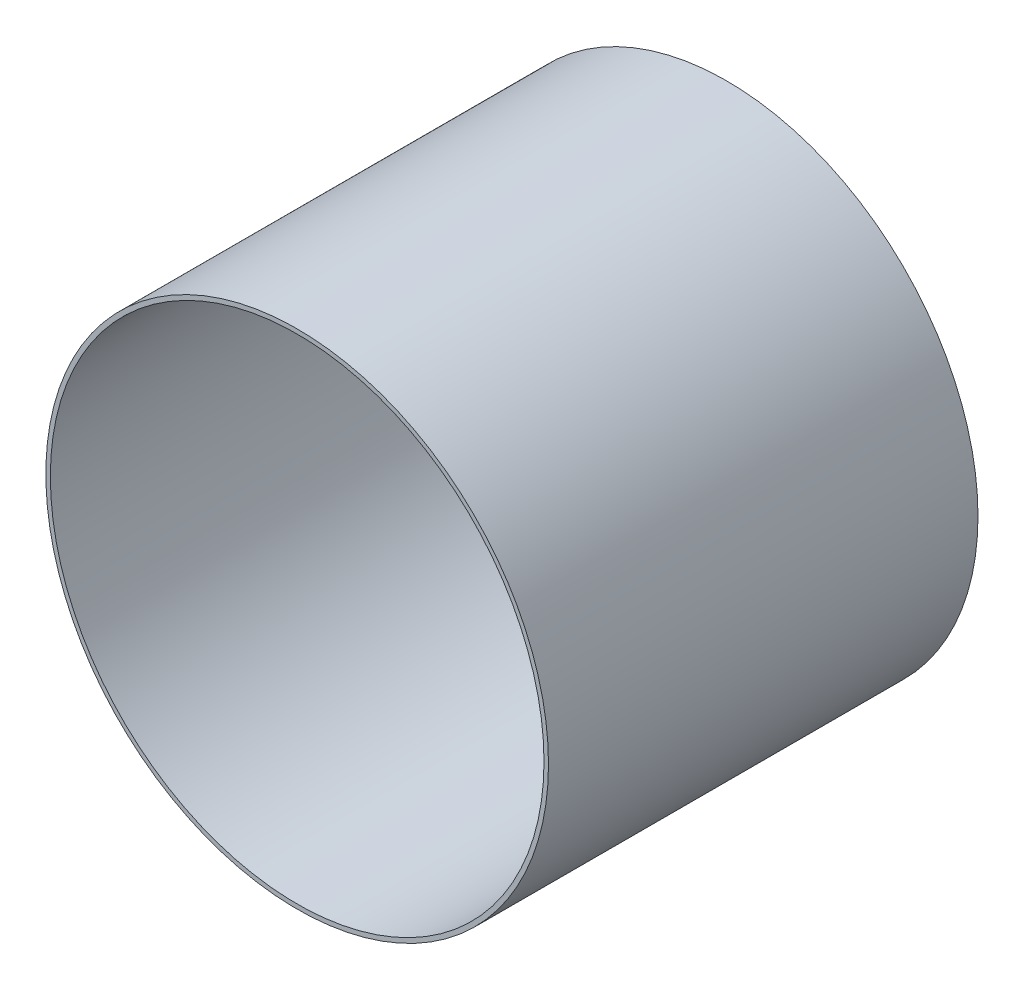
SolidWorks part; units mm, degrees
ref_plane "Front Plane" through (0, 0, 0) normal (0, 0, 1) x (1, 0, 0)
ref_plane "Top Plane" through (0, 0, 0) normal (0, 1, 0) x (1, 0, 0)
ref_plane "Right Plane" through (0, 0, 0) normal (1, 0, 0) x (0, 0, -1)
sketch "Sketch1" plane through (0, 0, 0) normal (0, 0, 1) x (1, 0, 0)
  circle A0 centre (0, 0) radius 71.12
  circle A1 centre (0, 0) radius 69.85
  dimension "D1" = 139.7
  dimension "D2" = 142.24
extrude "Extrude1" add sketch "Sketch1" along normal blind 121.539
